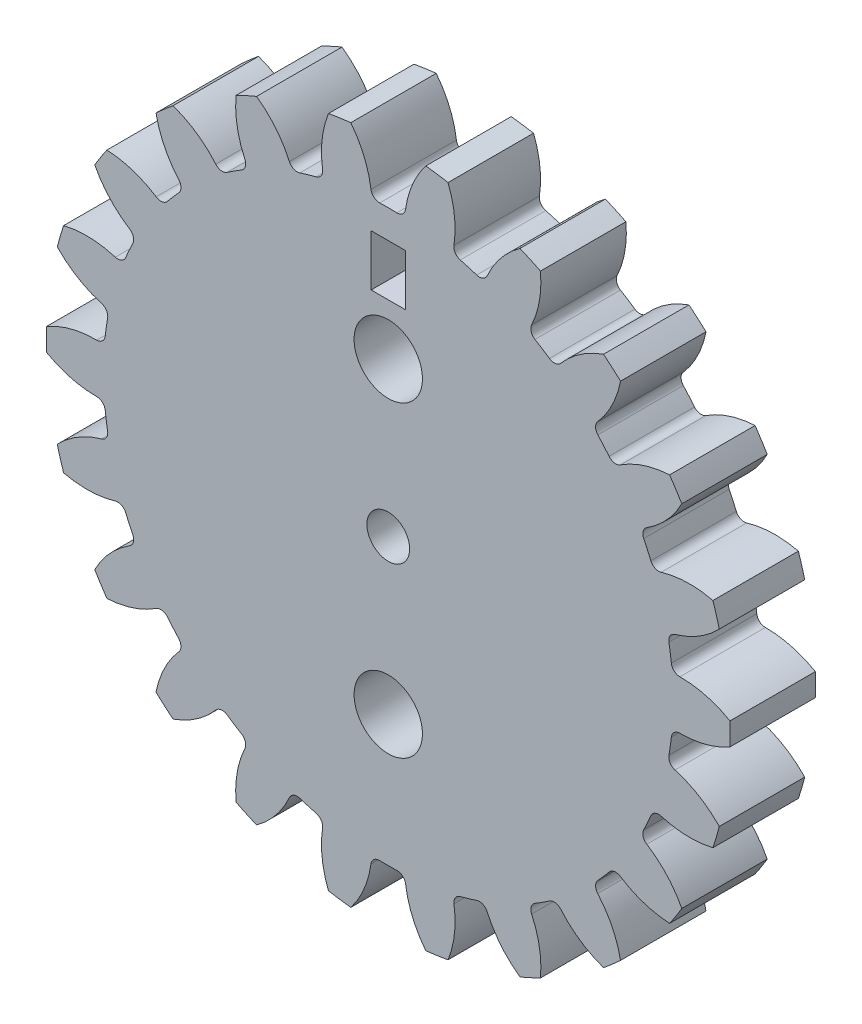
SolidWorks part; units mm, degrees
ref_plane "Front" through (0, 0, 0) normal (0, 0, 1) x (1, 0, 0)
ref_plane "Top" through (0, 0, 0) normal (0, 1, 0) x (1, 0, 0)
ref_plane "Right" through (0, 0, 0) normal (1, 0, 0) x (0, 0, -1)
sketch "Sketch1" plane through (0, 0, 0) normal (0, 0, 1) x (1, 0, 0)
  circle A0 centre (0, 0) radius 16.6667
  circle A1 centre (0, 0) radius 20
  circle A2 centre (0, 0) radius 18.3333
  dimension "D1" = 40
  dimension "D2" = 33.3333
  dimension "D3" = 36.6667
extrude "Boss-Extrude1" add sketch "Sketch1" along normal mid plane 5 contours A1
sketch "Sketch3" plane through (0, 0, 0) normal (0, 0, 1) x (1, 0, 0)
  line L0 (0, 0) -> (0, 20) construction
  line L1 (0, 0) -> (-0.9677, 16.6386) construction
  line L2 (-1.3079, 18.2866) -> (1.3079, 18.2866) construction
  line L3 (-1.8986, 19.9097) -> (0, 14.6932) construction
  line L4 (0, 0) -> (2.8463, 19.7964) construction
  line L5 (1.3079, 18.2866) -> (3.897, 17.9144) construction
  arc A0 (-0.9677, 16.6386) -> (0.9677, 16.6386) centre (0, 0) cw
  arc A4 (2.1919, 19.8795) -> (-2.1919, 19.8795) centre (0, 0) ccw
  circle A5 centre (0, 0) radius 20 construction
  arc A7 (-2.1919, 19.8795) -> (-0.9677, 16.6386) centre (-6.7617, 16.3016) cw
  arc A10 (2.1919, 19.8795) -> (0.9677, 16.6386) centre (6.7617, 16.3016) ccw
  circle A11 centre (0, 0) radius 16.6667 construction
  circle A12 centre (0, 0) radius 18.3333 construction
  dimension "D1" = 20
  dimension "D2" = 8.182
extrude "Cut-Extrude1" cut sketch "Sketch3" against normal through all both and the other way through all
fillet "Fillet2" radius 0.5 2 edges at (0.9677, 16.6386, 0) (-0.9677, 16.6386, 0)
pattern_circular "CirPattern1" count 22 over 360 about axis through (0, 0, 0) along (0, 0, 1) of "Cut-Extrude1", "Fillet2"
sketch "Sketch4" plane through (0, 0, 0) normal (0, 0, 1) x (1, 0, 0)
  circle A0 centre (0, 0) radius 1.25
  dimension "D1" = 2.5
extrude "String_Hole" cut sketch "Sketch4" against normal through all both and the other way through all
sketch "Sketch5" plane through (0, 0, 0) normal (0, 0, 1) x (1, 0, 0)
  line L0 (0, -9) -> (0, 9) construction
  circle A0 centre (0, 9) radius 2
  circle A1 centre (0, -9) radius 2
  dimension "D2" = 4
  dimension "D1" = 18
extrude "To_Knuckle_Mount" cut sketch "Sketch5" against normal through all both and the other way through all
sketch "Sketch7" plane through (0, 0, 2.5) normal (0, 0, 1) x (1, 0, 0)
  line L0 (0, 0) -> (0, 20) construction
  line L1 (-1, 12) -> (1, 12)
  line L2 (-1, 12) -> (-1, 15)
  line L3 (-1, 15) -> (1, 15)
  line L4 (1, 12) -> (1, 15)
  line L5 (-1, 12) -> (1, 15) construction
  line L6 (-1, 15) -> (1, 12) construction
  circle A0 centre (0, 9) radius 2 construction
  point P0 (0, 13.5)
  dimension "D1" = 2
  dimension "D2" = 3
  dimension "D3" = 3
extrude "For_Alignment" cut sketch "Sketch7" against normal blind 2
equation "\"od\"= 40'outside diameter"
equation "\"n\"= 22'number of teeth"
equation "\"m\"= \"od\" / ( \"n\" + 2 )'module"
equation "\"p\"= \"m\" * pi'pitch"
equation "\"d\"= \"m\" * \"n\"'primitive diameter"
equation "\"da\"= \"d\" + 2 * \"m\"'head diamater"
equation "\"df\"= \"d\" - 2 * \"m\"'foot diameter"
equation "\"D1@Sketch1\"=\"od\""
equation "\"D2@Sketch1\"=\"df\""
equation "\"D3@Sketch1\"=\"d\""
equation "\"D2@Sketch3\"=180/\"n\""
equation "\"D1@Fillet2\"=.3*\"m\""
equation "\"D1@CirPattern1\"=\"n\""
